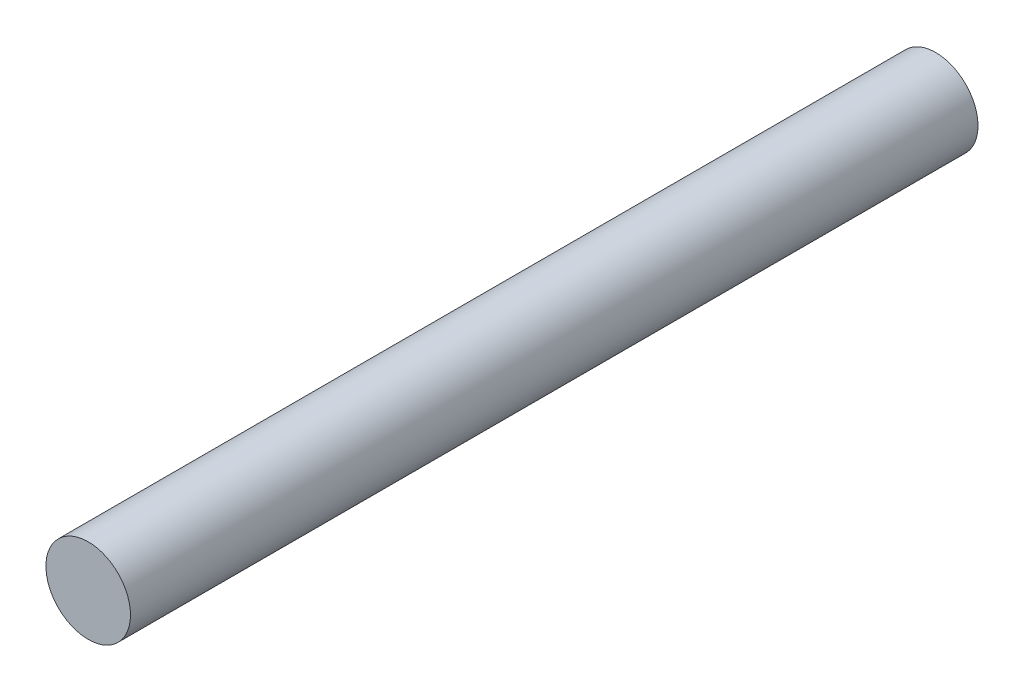
SolidWorks part; units mm, degrees
ref_plane "前视基准面" through (0, 0, 0) normal (0, 0, 1) x (1, 0, 0)
ref_plane "上视基准面" through (0, 0, 0) normal (0, 1, 0) x (1, 0, 0)
ref_plane "右视基准面" through (0, 0, 0) normal (1, 0, 0) x (0, 0, -1)
other "Configuration Table"
sketch "草图1" plane through (0, 0, 0) normal (0, 0, 1) x (1, 0, 0)
  circle A0 centre (0, 0) radius 2
  dimension "diameter" = 4
extrude "Driver_power_cable_envelope" add sketch "草图1" along normal blind 40.08
